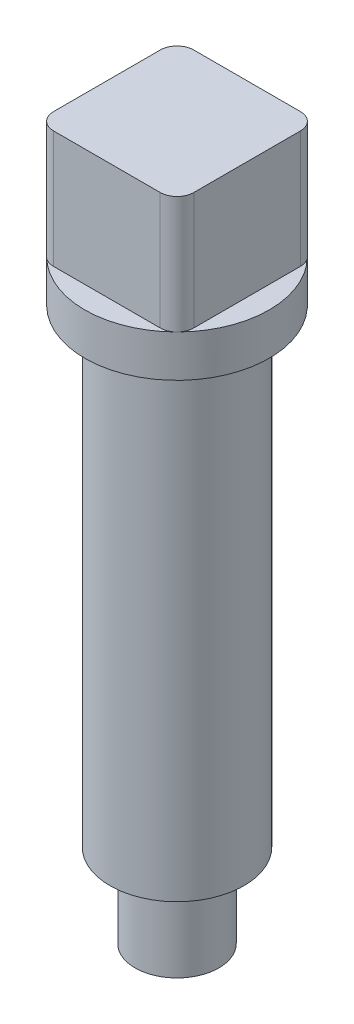
SolidWorks part; units mm, degrees
ref_plane "Ön Düzlem" through (0, 0, 0) normal (0, 0, 1) x (1, 0, 0)
ref_plane "Üst Düzlem" through (0, 0, 0) normal (0, 1, 0) x (1, 0, 0)
ref_plane "Sağ Düzlem" through (0, 0, 0) normal (1, 0, 0) x (0, 0, -1)
sketch "Çizim2" plane through (0, 0, 0) normal (0, 0, 1) x (1, 0, 0)
  line L0 (0, 0) -> (5, 0)
  line L1 (5, 0) -> (5, 10)
  line L2 (5, 10) -> (8, 10)
  line L3 (8, 10) -> (8, 66)
  line L4 (8, 66) -> (11, 66)
  line L5 (11, 66) -> (11, 71)
  line L6 (11, 71) -> (0, 71)
  line L7 (0, 71) -> (0, 0) construction
  line L8 (0, 0) -> (0, 71)
  point P8 (0, 0)
  dimension "D1" = 5
  dimension "D2" = 56
  dimension "D3" = 10
  dimension "D4" = 10
  dimension "D5" = 16
  dimension "D6" = 22
revolve "Döndür1" add sketch "Çizim2" angle 360 about L7
cosmetic thread "Kozmetik Diş Açma1" parameters "D2"=13.797
sketch "Çizim3" plane through (0, 71, 0) normal (0, 1, 0) x (1, 0, 0)
  line L1 (-6.364, 8.364) -> (6.364, 8.364)
  line L2 (-8.364, 6.364) -> (-8.364, -6.364)
  line L3 (-6.364, -8.364) -> (6.364, -8.364)
  line L4 (8.364, 6.364) -> (8.364, -6.364)
  line L5 (-8.364, 8.364) -> (8.364, -8.364) construction
  line L6 (-8.364, -8.364) -> (8.364, 8.364) construction
  arc A0 (6.364, 8.364) -> (8.364, 6.364) centre (6.364, 6.364) cw
  arc A1 (-8.364, -6.364) -> (-6.364, -8.364) centre (-6.364, -6.364) ccw
  arc A2 (-6.364, 8.364) -> (-8.364, 6.364) centre (-6.364, 6.364) ccw
  arc A3 (6.364, -8.364) -> (8.364, -6.364) centre (6.364, -6.364) ccw
  circle A4 centre (0, 0) radius 11 construction
  point P0 (0, 0)
  dimension "D1" = 2
extrude "Yükseklik-Ekstrüzyon1" add sketch "Çizim3" along normal blind 14
